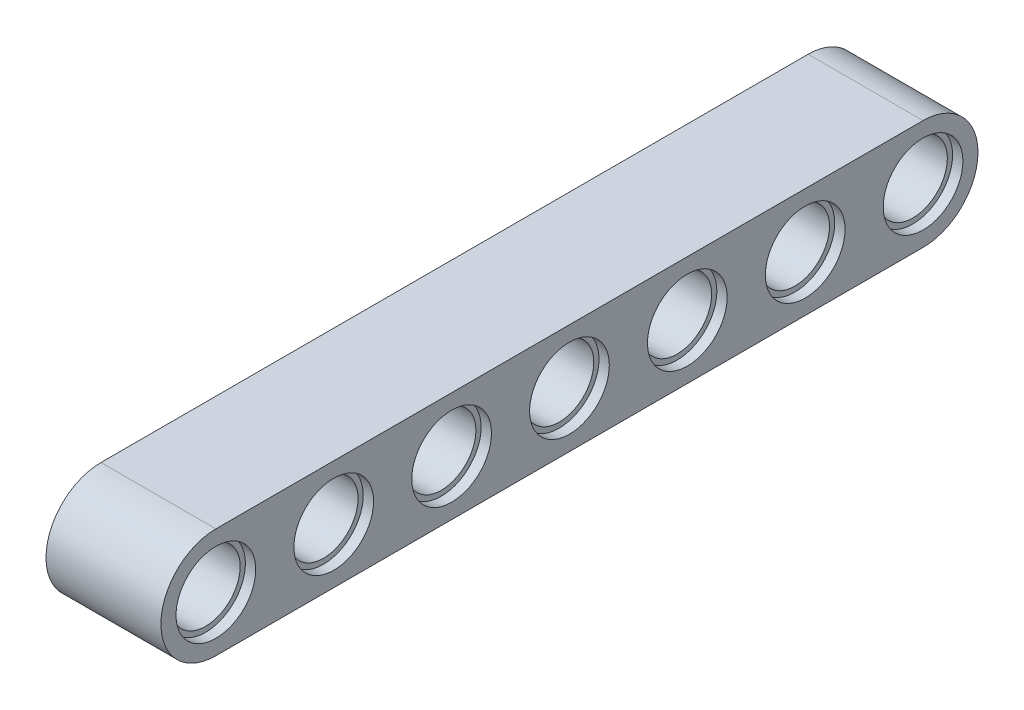
SolidWorks part; units mm, degrees
ref_plane "Front Plane" through (0, 0, 0) normal (0, 0, 1) x (1, 0, 0)
ref_plane "Top Plane" through (0, 0, 0) normal (0, 1, 0) x (1, 0, 0)
ref_plane "Right Plane" through (0, 0, 0) normal (1, 0, 0) x (0, 0, -1)
sketch "Sketch1" plane through (0, 0, 0) normal (1, 0, 0) x (0, 0, -1)
  line L0 (-24, 0) -> (24, 0) construction
  line L1 (-24, 3.73) -> (24, 3.73) construction
  line L2 (-24, 3.73) -> (-24, -3.73) construction
  line L3 (-24, -3.73) -> (24, -3.73) construction
  line L4 (24, 3.73) -> (24, -3.73) construction
  line L5 (-24, 3.73) -> (24, -3.73) construction
  line L6 (-24, -3.73) -> (24, 3.73) construction
  line L8 (-24, -3.73) -> (24, -3.73)
  line L10 (-24, 3.73) -> (24, 3.73)
  line L12 (-24, -3.73) -> (24, 3.73) construction
  line L13 (-24, 3.73) -> (24, -3.73) construction
  circle A0 centre (-24, 0) radius 2.35
  circle A1 centre (-16, 0) radius 2.35
  circle A2 centre (-8, 0) radius 2.35
  circle A3 centre (0, 0) radius 2.35
  circle A4 centre (8, 0) radius 2.35
  circle A5 centre (16, 0) radius 2.35
  circle A6 centre (24, 0) radius 2.35
  arc A12 (-24, 3.73) -> (-24, -3.73) centre (-24, 0) ccw
  arc A13 (24, -3.73) -> (24, 3.73) centre (24, 0) ccw
  point P0 (0, 0)
  point P9 (0, 0)
  point P11 (0, 0)
  dimension "D3" = 4.7
  dimension "D5" = 8
  dimension "D1" = 48
  dimension "D2" = 7.46
  dimension "D4" = 7
extrude "Boss-Extrude1" add sketch "Sketch1" along normal blind 7.8
sketch "Sketch2" plane through (0, 0, 0) normal (-1, 0, 0) x (0, 0, 1)
  circle A0 centre (-24, 0) radius 2.705
  circle A1 centre (-16, 0) radius 2.705
  circle A2 centre (-8, 0) radius 2.705
  circle A3 centre (0, 0) radius 2.705
  circle A4 centre (8, 0) radius 2.705
  circle A5 centre (16, 0) radius 2.705
  circle A6 centre (24, 0) radius 2.705
  point P3 (0, 0)
  dimension "D1" = 5.41
  dimension "D3" = 8
  dimension "D2" = 7
extrude "Cut-Extrude2" cut sketch "Sketch2" against normal blind 0.7
sketch "Sketch3" plane through (7.8, 0, 0) normal (1, 0, 0) x (0, 0, -1)
  circle A0 centre (-24, 0) radius 2.705
  circle A1 centre (-16, 0) radius 2.705
  circle A2 centre (-8, 0) radius 2.705
  circle A3 centre (0, 0) radius 2.705
  circle A4 centre (8, 0) radius 2.705
  circle A5 centre (16, 0) radius 2.705
  circle A6 centre (24, 0) radius 2.705
  point P4 (0, 0)
  dimension "D1" = 5.41
  dimension "D3" = 8
  dimension "D2" = 7
extrude "Cut-Extrude3" cut sketch "Sketch3" against normal blind 0.7
